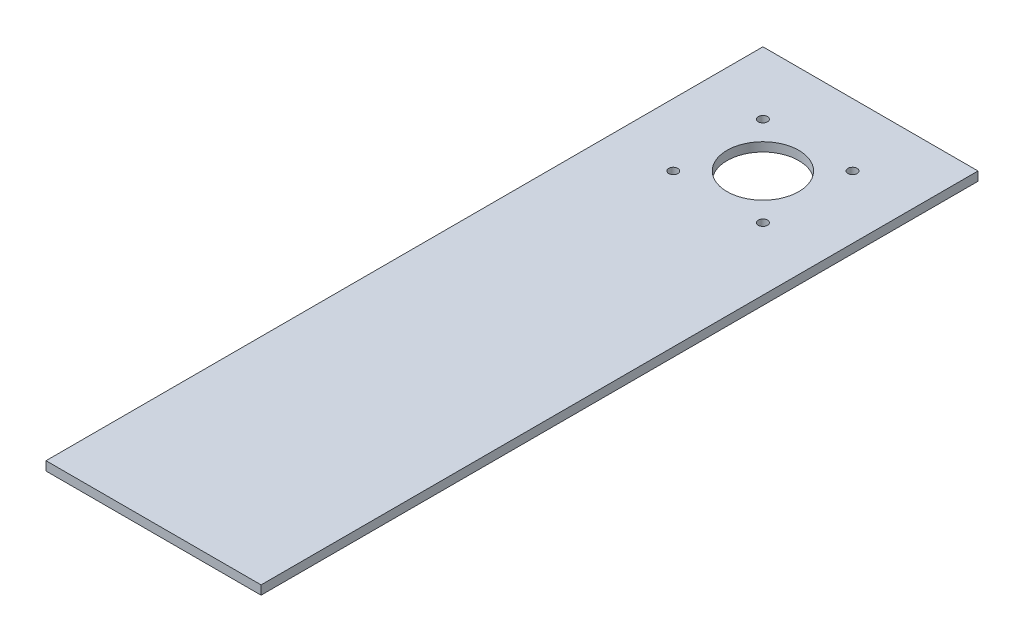
SolidWorks part; units mm, degrees
ref_plane "Front Plane" through (0, 0, 0) normal (0, 0, 1) x (1, 0, 0)
ref_plane "Top Plane" through (0, 0, 0) normal (0, 1, 0) x (1, 0, 0)
ref_plane "Right Plane" through (0, 0, 0) normal (1, 0, 0) x (0, 0, -1)
sketch "Sketch1" plane through (0, 0, 0) normal (0, 1, 0) x (1, 0, 0)
  line L1 (60, 60) -> (-60, 60)
  line L2 (60, 60) -> (60, -60)
  line L3 (60, -60) -> (-60, -60)
  line L4 (-60, 60) -> (-60, -60)
  line L5 (60, 60) -> (-60, -60) construction
  line L6 (60, -60) -> (-60, 60) construction
  circle A0 centre (-25, -25) radius 2.55
  circle A1 centre (25, -25) radius 2.55
  circle A2 centre (25, 25) radius 2.55
  circle A3 centre (-25, 25) radius 2.55
  circle A4 centre (0, 0) radius 20
  point P0 (0, 0)
  dimension "D3" = 5.1
  dimension "D4" = 5.1
  dimension "D5" = 5.1
  dimension "D6" = 5.1
  dimension "D11" = 40
  dimension "D2" = 120
  dimension "D7" = 50
  dimension "D8" = 50
  dimension "D9" = 50
  dimension "D10" = 50
extrude "Boss-Extrude1" add sketch "Sketch1" along normal blind 5
sketch "Sketch2" plane through (0, 0, 60) normal (0, 0, 1) x (1, 0, 0)
  line L1 (-60, 5) -> (60, 5)
  line L2 (-60, 5) -> (-60, 0)
  line L3 (-60, 0) -> (60, 0)
  line L4 (60, 5) -> (60, 0)
extrude "Boss-Extrude2" add sketch "Sketch2" along normal blind 280
